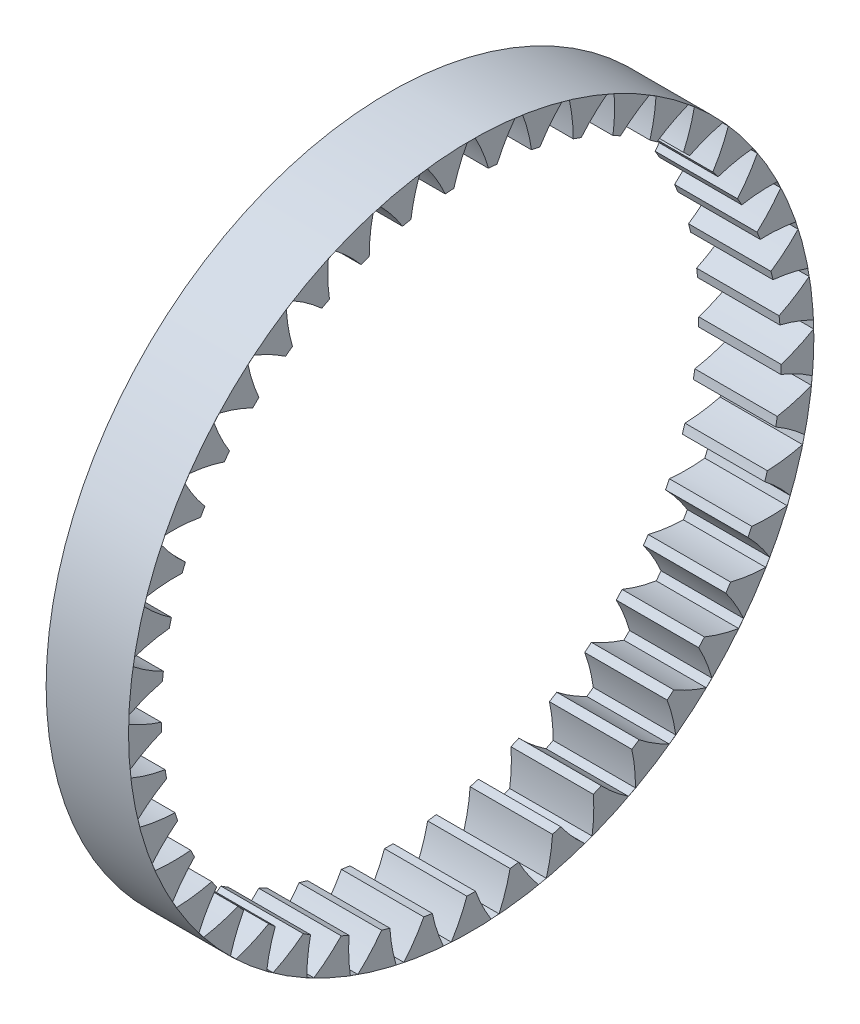
SolidWorks part; units mm, degrees
ref_plane "Plane1" through (0, 0, 0) normal (0, 0, 1) x (1, 0, 0)
ref_plane "Plane2" through (0, 0, 0) normal (0, 1, 0) x (1, 0, 0)
ref_plane "Plane3" through (0, 0, 0) normal (1, 0, 0) x (0, 0, -1)
sketch "HoldingSke" plane through (0, 0, 0) normal (0, 1, 0) x (1, 0, 0)
  line L0 (0, 0) -> (0.4041, -0.4041)
  line L1 (-15, 0) -> (100, 0) construction
  line L2 (0, 0) -> (-2.1039, 2.3779)
  line L3 (0, 0) -> (-11.863, 4.5341)
  line L4 (0, 0) -> (6.1066, 6.1066)
  line L5 (0, 0) -> (-23.7986, -8.8762)
  line L6 (0, 0) -> (-10.5278, -7.1032)
  line L7 (-2.1039, 2.3779) -> (3.3635, 27.1825)
  line L8 (-76.2, 4.1279) -> (-54.61, 4.1279)
  line L9 (-71.009, 38.7566) -> (-53.1078, 45.2721)
  line L10 (-76.2, 71.12) -> (104.1128, 71.12)
  line L11 (0, 0) -> (-10, 0)
  line L12 (-76.2, 101.6) -> (-76.147, 101.6)
  line L13 (24.9733, 27.94) -> (52.9518, 28.4284)
  line L14 (24.9733, 27.94) -> (24.9743, 27.94)
  line L15 (24.9733, 27.94) -> (100.4006, 29.5858)
  circle A0 centre (0, 0) radius 15
  circle A1 centre (0, 0) radius 12.7
  circle A2 centre (0, 0) radius 12.7
  dimension "MHD" = 25.4
  dimension "Hub_dia" = 25.4
  dimension "Diameter" = 30
  dimension "Num_teeth" = 45
  dimension "Pitch" = 0.5714
  dimension "Overall_len" = 25.4
  dimension "Show_teeth" = 45
  dimension "Thickness" = 12.7
  dimension "OAL" = 25.4001
  dimension "T_dim" = 21.59
  dimension "Ap" = 20
  dimension "H" = 19.05
  dimension "Pitch_radius" = 180.3128
  dimension "Width" = 10
  dimension "Backlash" = 0.053
  dimension "Addendum_fac" = 1
  dimension "Dedendum_fac" = 1.25
  dimension "Clearance_fac" = 0.25
  dimension "Dedendum_add" = 0.001
  dimension "Module" = 1.75
sketch "BasProSke" plane through (0, 0, 0) normal (0, 1, 0) x (1, 0, 0)
  line L0 (-10, 0) -> (60, 0) construction
  line L1 (0, 37.625) -> (0, 41.5889)
  line L2 (0, 37.625) -> (10, 37.625)
  line L3 (10, 37.625) -> (10, 41.5889)
  line L4 (10, 41.5889) -> (0, 41.5889)
  dimension "Thickness" = 10
  dimension "Diameter" = 83.1778
  dimension "Inside_diameter" = 75.25
revolve "Base-Revolve" add sketch "BasProSke" angle 360 about L0
sketch "TooCutSke" plane through (0, 0, 0) normal (1, 0, 0) x (0, 0, -1)
  line L3 (1.5067, 39.3462) -> (1.5067, 53.6633) construction
  line L4 (0, 0) -> (0, 59.563) construction
  line L5 (0, 0) -> (-4.7663, 68.1611) construction
  line L6 (-16.8397, 32.2041) -> (35.4277, 35.859) construction
  circle A0 centre (0, 0) radius 39.375 construction
  circle A1 centre (0, 0) radius 41.5635 construction
  circle A2 centre (0, 0) radius 33.3004 construction
  circle A3 centre (0, 0) radius 37.5996 construction
  arc A4 (2.1108, 37.5403) -> (0.4823, 41.5607) centre (-16.8397, 32.2041) ccw
  arc A5 (2.1108, 37.5403) -> (-2.1108, 37.5403) centre (0, 0) ccw
  arc A6 (0.4823, 41.5607) -> (-0.4823, 41.5607) centre (0, 0) ccw
  arc A7 (-0.4823, 41.5607) -> (-2.1108, 37.5403) centre (16.8397, 32.2041) ccw
  dimension "Pitch_dia" = 78.75
  dimension "Base_dia" = 66.6007
  dimension "Root_dia" = 83.127
  dimension "Overcut_dia" = 75.1992
  dimension "Flank_rad" = 19.6875
  dimension "Half_ang" = 4
  dimension "Half_CT" = 1.5067
extrude "ToothCut" cut sketch "TooCutSke" along normal through all
fillet "Breaks" [suppressed] radius 0.175
fillet "RootFillets" [suppressed] radius 0.4385
pattern_circular "TeethCuts" count 45 every 8 about axis through (-10, 0, 0) along (1, 0, 0) of "RootFillets", "Breaks", "ToothCut"
equation "' \"Module@HoldingSke\" = 6.35"
equation "' \"Num_teeth@HoldingSke\" = 24"
equation "' \"Ap@HoldingSke\" =  14.5"
equation "' \"Ap@HoldingSke\" = 14.5"
equation "' \"Width@HoldingSke\" = 12"
equation "' \"Diameter@HoldingSke\" = 8 * 25.4"
equation "' \"Show_teeth@HoldingSke\" = 100"
equation "' \"Backlash@HoldingSke\" = 0.009 * 25.4"
equation "' \"Addendum_fac@HoldingSke\" = 1.0"
equation "' \"Dedendum_fac@HoldingSke\" = 1.25"
equation "' \"Dedendum_add@HoldingSke\" = 0.00005 * 25.4"
equation "' \"Clearance_fac@HoldingSke\" = 0.25"
equation "\"Pitch@HoldingSke\" = 1 / \"Module@HoldingSke\" "
equation "\"Overcut_dia@TooCutSke\" = (\"Num_teeth@HoldingSke\" - 2 * \"Addendum_fac@HoldingSke\") / \"Pitch@HoldingSke\" - 0.002 * 25.4"
equation "\"Pitch_dia@TooCutSke\" = \"Num_teeth@HoldingSke\" / \"Pitch@HoldingSke\""
equation "\"Base_dia@TooCutSke\" = \"Num_teeth@HoldingSke\" / \"Pitch@HoldingSke\" * cos((\"Ap@HoldingSke\"  * 3.14159265 / 180)) * 0.90"
equation "\"Root_dia@TooCutSke\" = \"Num_teeth@HoldingSke\"  / \"Pitch@HoldingSke\" + 2 *  \"Dedendum_fac@HoldingSke\"/ \"Pitch@HoldingSke\" + \"Dedendum_add@HoldingSke\" * 2"
equation "\"Half_ang@TooCutSke\" = 180 / \"Num_teeth@HoldingSke\""
equation "\"Half_CT@TooCutSke\" = \"Num_teeth@HoldingSke\" / \"Pitch@HoldingSke\" * sin((3.14159265 / 2 / \"Num_teeth@HoldingSke\")) / 2 + 10 * \"Backlash@HoldingSke\" / 4"
equation "\"Flank_rad@TooCutSke\" = \"Num_teeth@HoldingSke\" / \"Pitch@HoldingSke\" / 4"
equation "\"Radius@RootFillets\"= \"Clearance_fac@HoldingSke\" / \"Pitch@HoldingSke\" + \"Dedendum_add@HoldingSke\""
equation "\"Break_rad@Breaks\" = 0.02 / \"Pitch@HoldingSke\" * 5"
equation "\"Num_teeth@TeethCuts\" = int( \"Show_teeth@HoldingSke\" ) + 1"
equation "\"Num_teeth@TeethCuts\" = ((sgn( \"Num_teeth@TeethCuts\" - \"Num_teeth@HoldingSke\" )-1)*( \"Num_teeth@TeethCuts\" - \"Num_teeth@HoldingSke\" ))/-2+ \"Num_teeth@HoldingSke\""
equation "\"Num_teeth@TeethCuts\" = ((sgn( \"Num_teeth@TeethCuts\" - 2.0)+1)*( \"Num_teeth@TeethCuts\" - 2.0))/2 +2.0"
equation "\"Angle@TeethCuts\" = 360.0 / \"Num_teeth@HoldingSke\""
equation "\"Diameter@BasProSke\" = \"Num_teeth@HoldingSke\"  / \"Pitch@HoldingSke\" + 2 *  \"Dedendum_fac@HoldingSke\"/ \"Pitch@HoldingSke\" + \"Dedendum_add@HoldingSke\" * 2 + 0.002 * 25.4"
equation "\"Diameter@BasProSke\" = ((sgn( \"Diameter@BasProSke\"  - \"Diameter@HoldingSke\" )+1)*( \"Diameter@BasProSke\"  - \"Diameter@HoldingSke\" ))/2 + \"Diameter@HoldingSke\""
equation "\"Inside_diameter@BasProSke\" =  (\"Num_teeth@HoldingSke\" - 2 * \"Addendum_fac@HoldingSke\") / \"Pitch@HoldingSke\" "
equation "\"Thickness@BasProSke\"  = \"Width@HoldingSke\""
